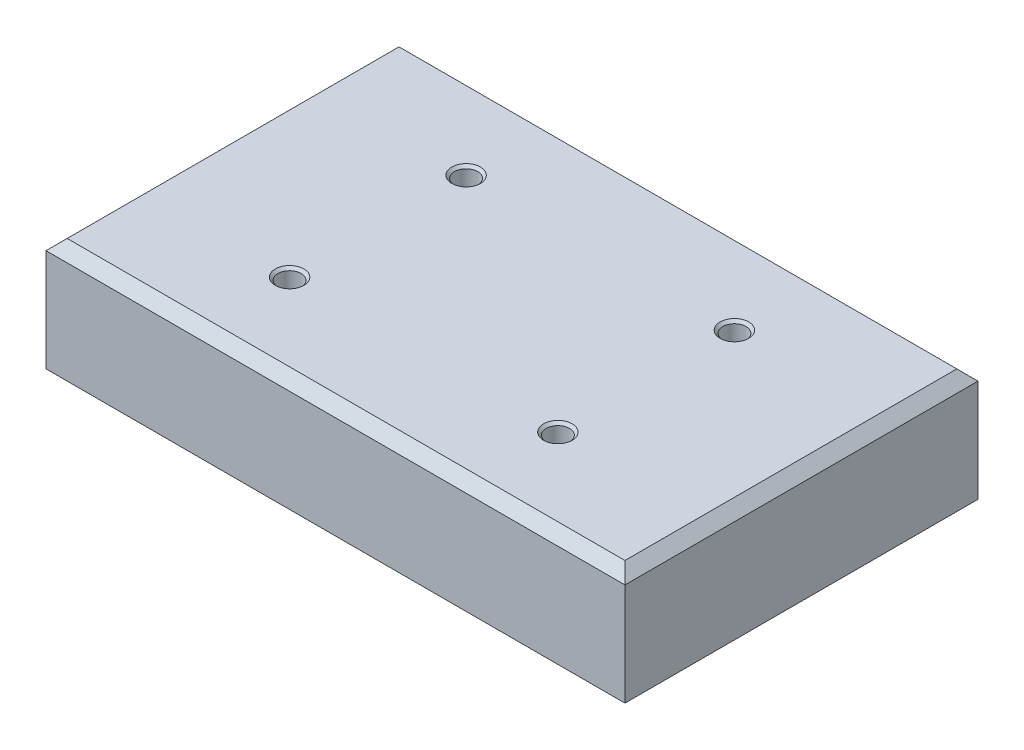
SolidWorks part; units mm, degrees
ref_plane "Front Plane" through (0, 0, 0) normal (0, 0, 1) x (1, 0, 0)
ref_plane "Top Plane" through (0, 0, 0) normal (0, 1, 0) x (1, 0, 0)
ref_plane "Right Plane" through (0, 0, 0) normal (1, 0, 0) x (0, 0, -1)
sketch "Sketch1" plane through (0, 0, 0) normal (0, 1, 0) x (1, 0, 0)
  line L1 (-41, 25) -> (41, 25)
  line L2 (-41, 25) -> (-41, -25)
  line L3 (-41, -25) -> (41, -25)
  line L4 (41, 25) -> (41, -25)
  line L5 (-41, 25) -> (41, -25) construction
  line L6 (-41, -25) -> (41, 25) construction
  point P0 (0, 0)
  dimension "D1" = 50
  dimension "D2" = 82
extrude "Boss-Extrude1" add sketch "Sketch1" along normal blind 16
hole_wizard "M4 Tapped Hole1" positions "Sketch2" profile "Sketch3" tap size "M4" standard "DIN"
sketch "Sketch2" plane through (0, 16, 0) normal (0, 1, 0) x (1, 0, 0)
  line L0 (0, 0) -> (0, 25) construction
  line L1 (41, 25) -> (-41, 25) construction
  line L4 (0, 0) -> (41, 0) construction
  line L5 (41, -25) -> (41, 25) construction
  point P0 (-19, 12.5)
  point P2 (-19, -12.5)
  point P4 (19, -12.5)
  point P6 (19, 12.5)
  point P8 (19, 12.5)
  point P10 (19, -12.5)
  point P36 (0, 0)
  point P37 (0, 0)
  dimension "D1" = 38
  dimension "25" = 25
sketch "Sketch3" plane through (-19, 16, -12.5) normal (1, 0, 0) x (0, 0, 1)
  line L0 (0, 0) -> (0, 8.9914)
  line L1 (0, 8.9914) -> (1.65, 8)
  line L2 (1.65, 8) -> (1.65, 0.375)
  line L3 (1.65, 0.375) -> (2.025, 0)
  line L5 (2.025, 0) -> (0, 0)
  line L6 (-1.65, 0.375) -> (-2.025, 0) construction
  line L10 (0, 8.9914) -> (-1.65, 8) construction
  line L11 (0, -6.35) -> (0, 107.95) construction
  dimension "Tap Drill Dia." = 3.3
  dimension "Tap Drill Depth" = 8
  dimension "Near C'Sink Dia." = 4.05
  dimension "Near C'Sink Angle" = 90
  dimension "Drill Angle" = 118
cosmetic thread "Hole Thread3" parameters "D1"=8, "D2"=4
cosmetic thread "Hole Thread4" parameters "D1"=8, "D2"=4
cosmetic thread "Hole Thread5" parameters "D1"=8, "D2"=4
cosmetic thread "Hole Thread6" parameters "D1"=8, "D2"=4
cosmetic thread "Hole Thread7" parameters "D1"=8, "D2"=4
cosmetic thread "Hole Thread8" parameters "D1"=8, "D2"=4
chamfer "Chamfer1" distance 1.5 angle 45 4 edges at (41, 16, 0) (0, 16, -25) (-41, 16, 0) (0, 16, 25)
